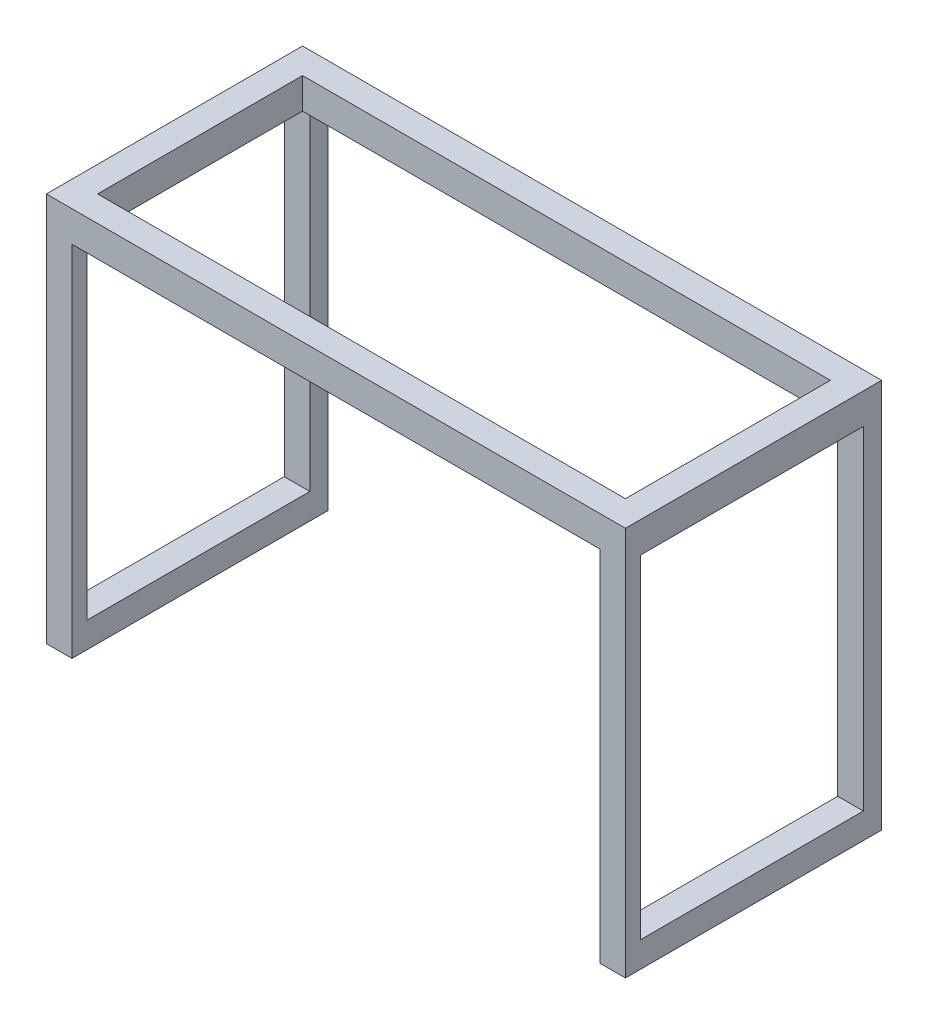
SolidWorks part; units mm, degrees
ref_plane "Front Plane" through (0, 0, 0) normal (0, 0, 1) x (1, 0, 0)
ref_plane "Top Plane" through (0, 0, 0) normal (0, 1, 0) x (1, 0, 0)
ref_plane "Right Plane" through (0, 0, 0) normal (1, 0, 0) x (0, 0, -1)
sketch "Sketch1" plane through (0, 0, 0) normal (0, 1, 0) x (1, 0, 0)
  line L1 (565, -250) -> (-565, -250)
  line L2 (565, -250) -> (565, 250)
  line L3 (565, 250) -> (-565, 250)
  line L4 (-565, -250) -> (-565, 250)
  line L5 (565, -250) -> (-565, 250) construction
  line L6 (565, 250) -> (-565, -250) construction
  point P0 (0, 0)
  dimension "D1" = 500
  dimension "D2" = 1130
extrude "Boss-Extrude1" add sketch "Sketch1" along normal blind 60
sketch "Sketch2" plane through (0, 60, 0) normal (0, 1, 0) x (1, 0, 0)
  line L0 (565, 250) -> (-565, 250) construction
  line L1 (515, -200) -> (-515, -200)
  line L2 (515, -200) -> (515, 200)
  line L3 (515, 200) -> (-515, 200)
  line L4 (-515, -200) -> (-515, 200)
  line L5 (515, -200) -> (-515, 200) construction
  line L6 (515, 200) -> (-515, -200) construction
  line L7 (-565, 250) -> (-565, -250) construction
  point P0 (0, 0)
  dimension "D1" = 50
  dimension "D2" = 50
  dimension "D3" = 400
  dimension "D4" = 1030
extrude "Cut-Extrude1" cut sketch "Sketch2" against normal blind 60
sketch "Sketch3" plane through (0, 0, 0) normal (0, -1, 0) x (-1, 0, 0)
  line L0 (-565, 250) -> (565, 250) construction
  line L1 (565, -250) -> (515, -250)
  line L2 (565, -250) -> (565, 250)
  line L3 (565, 250) -> (515, 250)
  line L4 (515, -250) -> (515, 250)
  line L5 (0, -501.9572) -> (0, 421.7262) construction
  line L6 (-565, 250) -> (-515, 250)
  line L7 (-565, -250) -> (-515, -250)
  line L8 (-515, -250) -> (-515, 250)
  line L9 (-565, -250) -> (-565, 250)
extrude "Boss-Extrude3" add sketch "Sketch3" along normal blind 700
sketch "Sketch5" plane through (-565, 0, 0) normal (-1, 0, 0) x (0, 0, 1)
  line L0 (0, 82.9384) -> (0, -738.617) construction
  line L1 (250, -700) -> (-250, -700) construction
  line L2 (-214.2734, 0) -> (220.5448, 0)
  line L3 (-214.2734, 0) -> (-214.2734, -650)
  line L4 (-214.2734, -650) -> (220.5448, -650)
  line L5 (220.5448, 0) -> (220.5448, -650)
  line L6 (-250, 60) -> (250, 60) construction
  dimension "D1" = 50
  dimension "D2" = 60
extrude "Cut-Extrude2" cut sketch "Sketch5" against normal blind 1902
